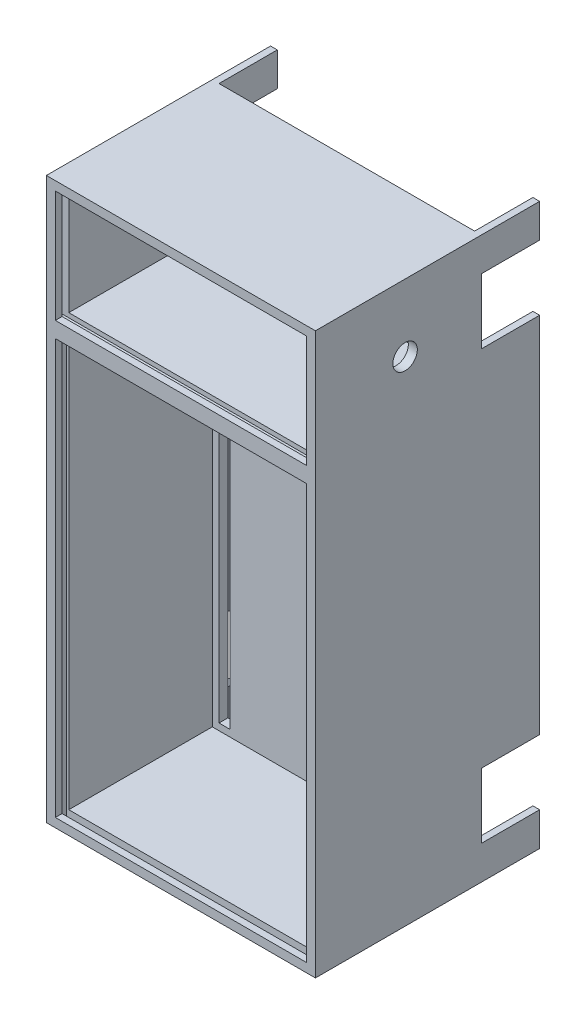
SolidWorks part; units mm, degrees
ref_plane "Plano frontal" through (0, 0, 0) normal (1, 0, 0) x (0, 1, 0)
ref_plane "Plano superior" through (0, 0, 0) normal (0, 0, 1) x (0, 1, 0)
ref_plane "Plano direito" through (0, 0, 0) normal (0, 1, 0) x (-1, 0, 0)
sketch "Esboço1" plane through (0, 0, 0) normal (0, 0, 1) x (0, 1, 0)
  line L1 (125, -60) -> (-125, -60)
  line L2 (125, -60) -> (125, 60)
  line L3 (125, 60) -> (-125, 60)
  line L4 (-125, -60) -> (-125, 60)
  line L5 (125, -60) -> (-125, 60) construction
  line L6 (125, 60) -> (-125, -60) construction
  point P0 (0, 0)
  dimension "D1" = 250
  dimension "D2" = 120
extrude "Ressalto-extrusão1" add sketch "Esboço1" along normal blind 100
sketch "Esboço2" plane through (0, 0, 100) normal (0, 0, 1) x (1, 0, 0)
  line L0 (60, 125) -> (-60, 125) construction
  line L1 (-56, 121) -> (56, 121)
  line L2 (-56, 121) -> (-56, 71)
  line L3 (-56, 71) -> (56, 71)
  line L4 (56, 121) -> (56, 71)
  line L5 (60, -125) -> (60, 125) construction
  dimension "D1" = 50
  dimension "D2" = 112
  dimension "D3" = 4
  dimension "D4" = 4
extrude "Corte-extrusão1" cut sketch "Esboço2" against normal blind 70
sketch "Esboço3" plane through (-60, 0, 0) normal (-1, 0, 0) x (0, -1, 0)
  line L0 (-125, 100) -> (125, 100) construction
  line L1 (-123, 97) -> (-69, 97)
  line L2 (-123, 97) -> (-123, 94)
  line L3 (-123, 94) -> (-69, 94)
  line L4 (-69, 97) -> (-69, 94)
  line L5 (-125, 100) -> (-125, 0) construction
  dimension "D1" = 54
  dimension "D2" = 3
  dimension "D3" = 3
  dimension "D4" = 2
extrude "Corte-extrusão2" cut sketch "Esboço3" against normal blind 118
sketch "Esboço5" plane through (0, 0, 100) normal (0, 0, 1) x (1, 0, 0)
  line L0 (-60, 125) -> (-60, -125) construction
  line L1 (-56, 64) -> (56, 64)
  line L2 (-56, 64) -> (-56, -121)
  line L3 (-56, -121) -> (56, -121)
  line L4 (56, 64) -> (56, -121)
  line L6 (-60, -125) -> (60, -125) construction
  dimension "D1" = 185
  dimension "D2" = 112
  dimension "D3" = 4
  dimension "D4" = 4
extrude "Corte-extrusão3" cut sketch "Esboço5" against normal blind 70
sketch "Esboço6" plane through (0, -125, 0) normal (0, -1, 0) x (1, 0, 0)
  line L0 (-60, 100) -> (-60, 0) construction
  line L1 (-57, 97) -> (57, 97)
  line L2 (-57, 97) -> (-57, 94)
  line L3 (-57, 94) -> (57, 94)
  line L4 (57, 97) -> (57, 94)
  line L5 (-60, 100) -> (60, 100) construction
  line L6 (60, 100) -> (60, 0) construction
  dimension "D1" = 3
  dimension "D2" = 3
  dimension "D3" = 3
  dimension "D4" = 3
extrude "Corte-extrusão4" cut sketch "Esboço6" against normal blind 192
sketch "Esboço7" plane through (0, -125, 0) normal (0, -1, 0) x (1, 0, 0)
  line L0 (-60, 0) -> (60, 0) construction
  line L1 (-57, 0) -> (57, 0)
  line L2 (-57, 0) -> (-57, 26)
  line L3 (-57, 26) -> (57, 26)
  line L4 (57, 0) -> (57, 26)
  line L5 (-60, 100) -> (-60, 0) construction
  line L6 (60, 100) -> (60, 0) construction
  dimension "D1" = 3
  dimension "D2" = 3
  dimension "26" = 26
extrude "Corte-extrusão5" cut sketch "Esboço7" against normal blind 500
sketch "Esboço8" plane through (0, 0, 30) normal (0, 0, 1) x (1, 0, 0)
  line L0 (-56, 64) -> (-56, -121) construction
  line L1 (-53, 61) -> (-48, 61)
  line L2 (-53, 61) -> (-53, -118)
  line L3 (-53, -118) -> (-48, -118)
  line L4 (-48, 61) -> (-48, -118)
  line L5 (56, 64) -> (-56, 64) construction
  line L6 (-56, -121) -> (56, -121) construction
  dimension "D1" = 5
  dimension "D2" = 3
  dimension "D3" = 3
  dimension "D4" = 3
extrude "Corte-extrusão6" cut sketch "Esboço8" against normal blind 500
mirror "Espelhar1" about plane through (0, 0, 0) normal (1, 0, 0) of "Corte-extrusão6"
sketch "Esboço9" plane through (-60, 0, 0) normal (-1, 0, 0) x (0, -1, 0)
  line L2 (-125, 0) -> (125, 0) construction
  line L3 (-110, 0) -> (-81, 0)
  line L4 (-110, 0) -> (-110, 26)
  line L5 (-110, 26) -> (-81, 26)
  line L6 (-81, 0) -> (-81, 26)
  line L7 (-125, 100) -> (-125, 0) construction
  point P4 (-112.7363, 0)
  dimension "D1" = 15
  dimension "D2" = 26
  dimension "29" = 29
extrude "Corte-extrusão7" cut sketch "Esboço9" against normal blind 500
mirror "Espelhar2" about plane through (0, 0, 0) normal (0, 1, 0) of "Corte-extrusão7"
sketch "Esboço10" plane through (60, 0, 0) normal (1, 0, 0) x (0, 1, 0)
  line L0 (-125, 100) -> (125, 100) construction
  line L1 (125, 100) -> (125, 0) construction
  circle A0 centre (95, 60) radius 5.45
  dimension "D1" = 10.9
  dimension "D2" = 40
  dimension "D3" = 30
extrude "Corte-extrusão8" cut sketch "Esboço10" against normal blind 10
